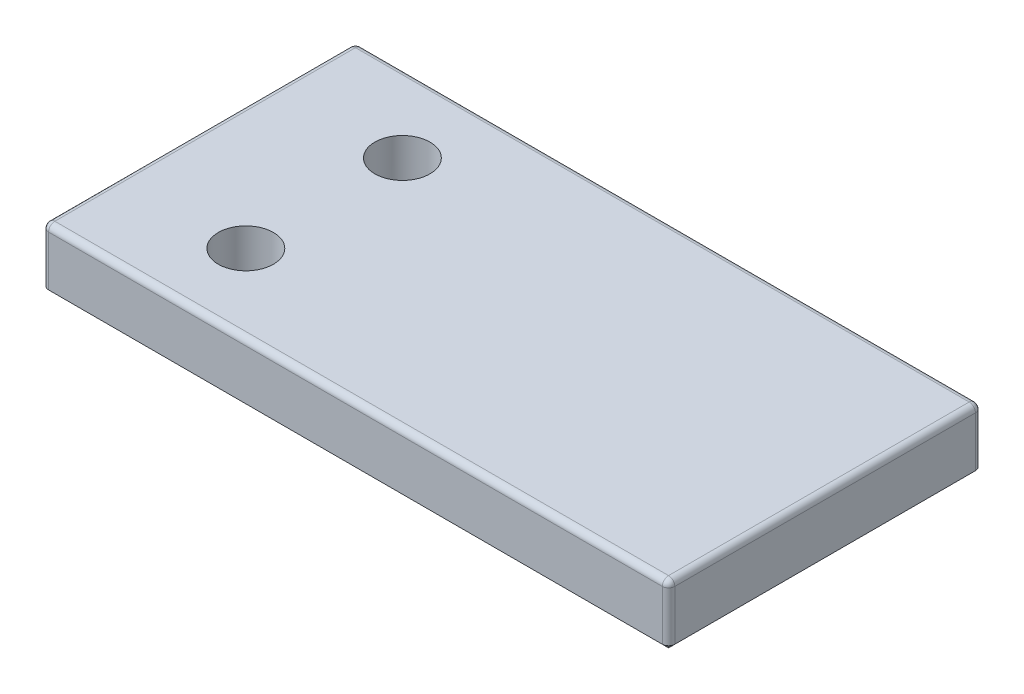
SolidWorks part; units mm, degrees
ref_plane "前基準面" through (0, 0, 0) normal (0, 0, 1) x (1, 0, 0)
ref_plane "上基準面" through (0, 0, 0) normal (0, 1, 0) x (1, 0, 0)
ref_plane "右基準面" through (0, 0, 0) normal (1, 0, 0) x (0, 0, -1)
sketch "草圖1" plane through (0, 0, 0) normal (0, 1, 0) x (1, 0, 0)
  line L1 (0, 0) -> (100, 0)
  line L2 (0, 0) -> (0, 50)
  line L3 (0, 50) -> (100, 50)
  line L4 (100, 0) -> (100, 50)
  dimension "D1" = 100
  dimension "D2" = 50
extrude "填料-伸長1" add sketch "草圖1" along normal blind 10
sketch "草圖2" plane through (0, 10, 0) normal (0, 1, 0) x (1, 0, 0)
  line L0 (0, 0) -> (100, 0) construction
  line L1 (20, 37.5) -> (80, 37.5)
  line L2 (20, 37.5) -> (20, 12.5)
  line L3 (20, 12.5) -> (80, 12.5)
  line L4 (80, 37.5) -> (80, 12.5)
  line L5 (0, 50) -> (0, 0) construction
  dimension "D1" = 25
  dimension "D2" = 12.5
  dimension "D3" = 20
  dimension "D4" = 60
hole_wizard "M10x1.25 螺紋孔1" positions "3D草圖1" profile "草圖3" tap size "M10x1.25" standard "ISO"
sketch3d "3D草圖1"
  point P0 (20, 10, -37.5)
  point P3 (20, 10, -12.5)
sketch "草圖3" plane through (20, 10, -37.5) normal (1, 0, 0) x (0, 0, 1)
  line L0 (0, 0) -> (0, 26.3938)
  line L1 (0, 26.3938) -> (4.4, 23.75)
  line L2 (4.4, 23.75) -> (4.4, 0)
  line L5 (4.4, 0) -> (0, 0)
  line L10 (0, 26.3938) -> (-4.4, 23.75) construction
  line L11 (0, -6.35) -> (0, 107.95) construction
  dimension "螺孔鑽直徑" = 8.8
  dimension "螺孔鑽深度" = 23.75
  dimension "導頭角度" = 118
cosmetic thread "鑽孔螺紋1" parameters "D1"=10, "D2"=10
cosmetic thread "鑽孔螺紋2" parameters "D1"=10, "D2"=10
fillet "圓角1" radius 1 4 edges at (100, 5, -50) (0, 5, -50) (0, 5, 0) (100, 5, 0)
chamfer "導角1" distance 1 angle 45 8 edges at (50, 0, -50) (0.2929, 0, -49.7071) (99.7071, 0, -49.7071) (0, 0, -25) (100, 0, -25) (0.2929, 0, -0.2929) (99.7071, 0, -0.2929) (50, 0, 0)
fillet "圓角2" radius 1 8 edges at (0.2929, 10, -0.2929) (0, 10, -25) (0.2929, 10, -49.7071) (50, 10, -50) (99.7071, 10, -49.7071) (100, 10, -25) (99.7071, 10, -0.2929) (50, 10, 0)
